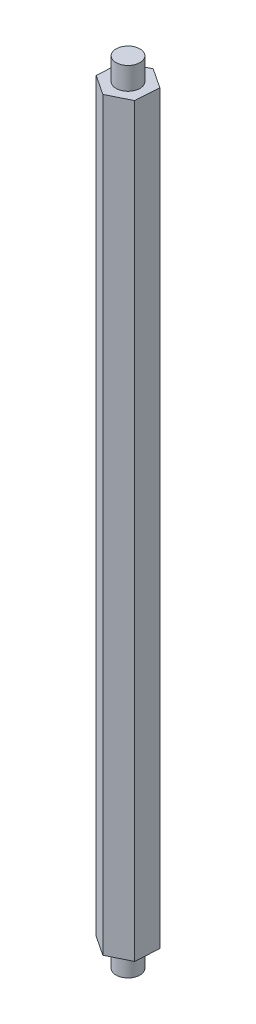
SolidWorks part; units mm, degrees
ref_plane "前视基准面" through (0, 0, 0) normal (0, 0, 1) x (1, 0, 0)
ref_plane "上视基准面" through (0, 0, 0) normal (0, 1, 0) x (1, 0, 0)
ref_plane "右视基准面" through (0, 0, 0) normal (1, 0, 0) x (0, 0, -1)
sketch "草图1" plane through (0, 0, 0) normal (0, 1, 0) x (1, 0, 0)
  circle A0 centre (0, 0) radius 1.6
  dimension "D1" = 3.2
extrude "凸台-拉伸1" add sketch "草图1" along normal blind 3
sketch "草图2" plane through (0, 3, 0) normal (0, 1, 0) x (1, 0, 0)
  line L1 (2.6526, -1.7614) -> (2.8517, 1.4165)
  line L2 (2.8517, 1.4165) -> (0.1992, 3.1779)
  line L3 (0.1992, 3.1779) -> (-2.6526, 1.7614)
  line L4 (-2.6526, 1.7614) -> (-2.8517, -1.4165)
  line L5 (-2.8517, -1.4165) -> (-0.1992, -3.1779)
  line L6 (-0.1992, -3.1779) -> (2.6526, -1.7614)
  circle A0 centre (0, 0) radius 2.7575 construction
extrude "凸台-拉伸2" add sketch "草图2" along normal blind 100
sketch "草图3" plane through (0, 103, 0) normal (0, 1, 0) x (1, 0, 0)
  circle A0 centre (0, 0) radius 1.6
  dimension "D1" = 3.2
extrude "凸台-拉伸3" add sketch "草图3" along normal blind 3
